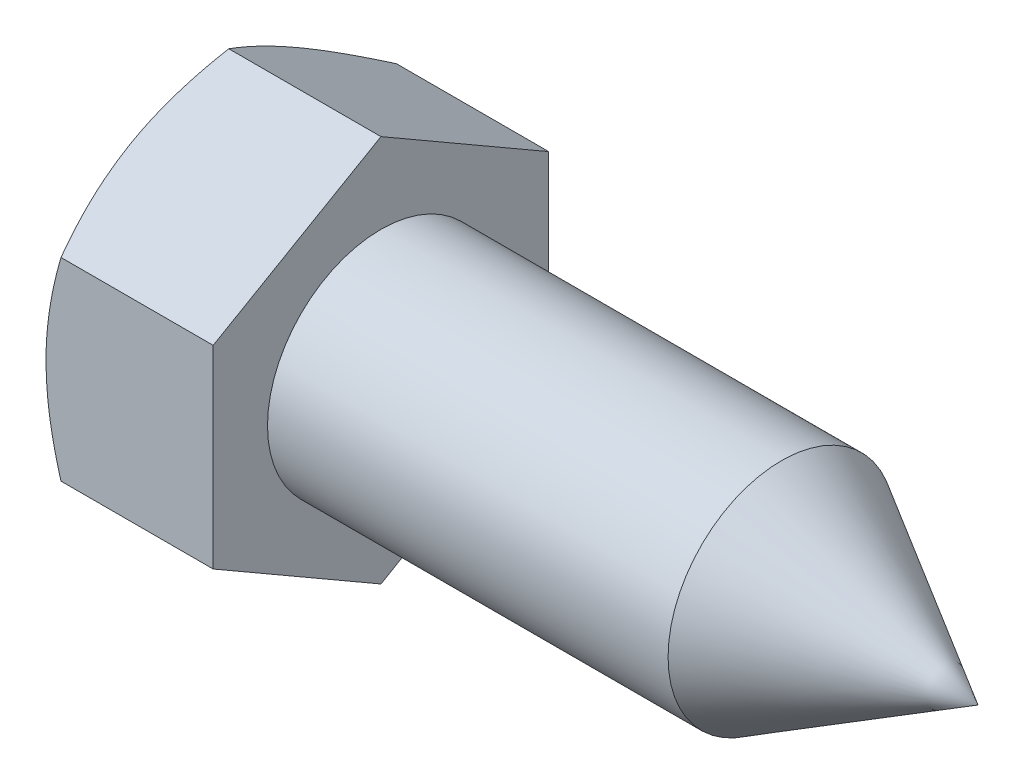
SolidWorks part; units mm, degrees
extrude "BaseHead" add sketch "Sketch1" along normal blind 3.556
sketch "Sketch1" plane through (0, 0, 0) normal (1, 0, 0) x (0, 0, -1)
  line L0 (3.5687, 2.0604) -> (3.5687, -2.0604)
  line L1 (-3.5687, 2.0604) -> (-3.5687, -2.0604)
  line L2 (3.5687, -2.0604) -> (0, -4.1208)
  line L3 (0, -4.1208) -> (-3.5687, -2.0604)
  line L4 (3.5687, 2.0604) -> (0, 4.1208)
  line L5 (0, 4.1208) -> (-3.5687, 2.0604)
  dimension "Width_flats" = 7.1374
  dimension "D2" = 120
  dimension "D3" = 3.5687
  dimension "D4" = 3.5687
  dimension "D5" = 3.5687
material "Plain Carbon Steel"
ref_plane "Plane1" through (0, 0, 0) normal (0, 0, 1) x (1, 0, 0)
ref_plane "Plane2" through (0, 0, 0) normal (0, 1, 0) x (1, 0, 0)
ref_plane "Plane3" through (0, 0, 0) normal (1, 0, 0) x (0, 0, -1)
sketch "Sketch2" plane through (0, 0, 0) normal (0, 0, 1) x (1, 0, 0)
  line L0 (0, 2.0604) -> (0, -2.0604) construction
  line L1 (0, 0) -> (16.256, 0)
  line L2 (0, 0) -> (0, 2.413)
  line L3 (0, 2.413) -> (12.0766, 2.413)
  line L4 (16.256, 0) -> (12.0766, -2.413) construction
  line L6 (16.256, 0) -> (12.0766, 2.413)
  line L7 (0, 0) -> (120.65, 0) construction
  line L8 (0, -2.413) -> (12.0766, -2.413) construction
  line L9 (3.556, 4.1208) -> (3.556, 2.0604) construction
  dimension "Length" = 12.7
  dimension "Diameter" = 4.826
  dimension "Point_ang" = 60
revolve "BaseBody" add sketch "Sketch2" angle 360 about L7
sketch "Sketch3" plane through (0, 0, 0) normal (0, 0, 1) x (1, 0, 0)
  line L0 (0, 3.5687) -> (3.9849, 10.4708)
  line L1 (0, 4.1208) -> (0, 2.0604) construction
  line L2 (3.9849, 10.4708) -> (3.9849, 16.8208)
  line L3 (3.9849, 16.8208) -> (-12.7, 16.8208)
  line L4 (-12.7, 16.8208) -> (-12.7, 3.5687)
  line L5 (-12.7, 3.5687) -> (0, 3.5687)
  line L6 (0, 0) -> (99.06, 0) construction
  line L7 (3.556, 4.1208) -> (0, 4.1208) construction
  dimension "D1" = 3.5687
  dimension "D2" = 6.35
  dimension "D3" = 12.7
  dimension "D4" = 6.35
  dimension "Head_ch_ang" = 30
revolve "HeadChamfer" cut sketch "Sketch3" angle 360 about L6
fillet "HeadFillet" [suppressed] radius 0.762
equation "\"D3@Sketch1\" = \"Width_flats@Sketch1\" / 2"
equation "\"D4@Sketch1\" = \"D3@Sketch1\""
equation "\"D5@Sketch1\" = \"D4@Sketch1\""
equation "\"D1@Sketch3\" = \"Width_flats@Sketch1\" / 2"
